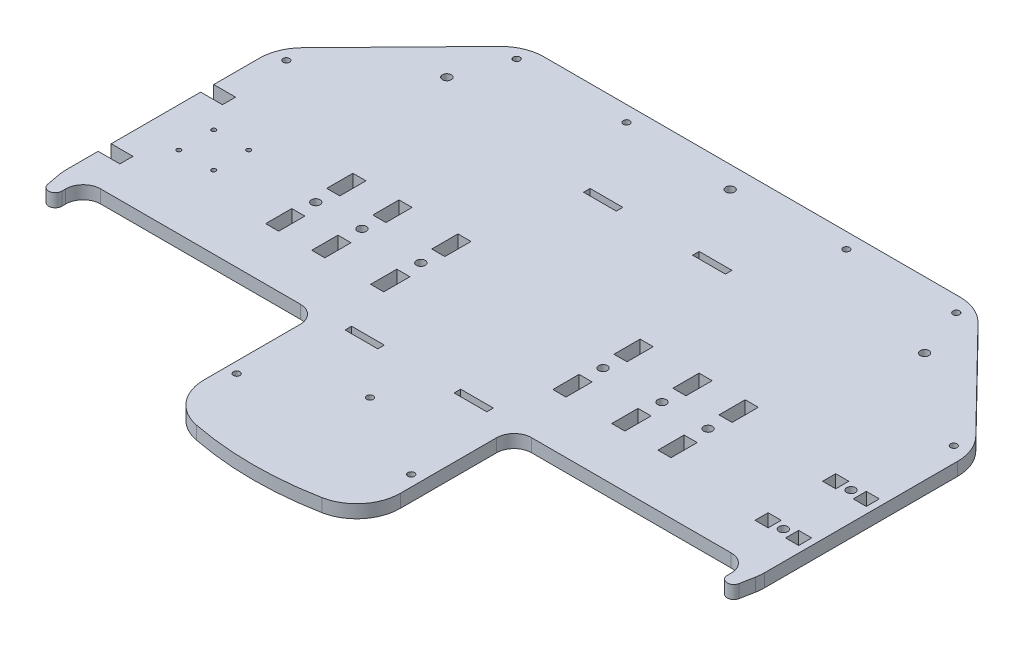
SolidWorks part; units mm, degrees
material "Hêtre"
ref_plane "Plan de face" through (0, 0, 0) normal (0, 0, 1) x (1, 0, 0)
ref_plane "Plan de dessus" through (0, 0, 0) normal (0, 1, 0) x (1, 0, 0)
ref_plane "Plan de droite" through (0, 0, 0) normal (1, 0, 0) x (0, 0, -1)
sketch "Esquisse1" plane through (0, 0, 0) normal (0, 1, 0) x (1, 0, 0)
  line L0 (-159.6514, 61.9965) -> (-151.003, 16.2822)
  line L1 (131.3515, 0) -> (50.1768, 0)
  line L2 (0, 0) -> (0, 220) construction
  line L3 (95.3188, 220) -> (-95.3188, 220)
  line L4 (-160, 65.7142) -> (-160, 154.2858)
  line L5 (-154.3028, 168.2654) -> (-109.6216, 213.9796)
  line L6 (0, 110) -> (-160, 110) construction
  line L7 (154.3028, 168.2654) -> (109.6216, 213.9796)
  line L8 (160, 65.7142) -> (160, 154.2858)
  line L9 (159.6514, 61.9965) -> (151.003, 16.2822)
  line L10 (-50.1768, 0) -> (-131.3515, 0)
  arc A0 (-151.003, 16.2822) -> (-131.3515, 0) centre (-131.3515, 20) ccw
  arc A1 (-159.6514, 61.9965) -> (-160, 65.7142) centre (-140, 65.7142) cw
  arc A2 (-109.6216, 213.9796) -> (-95.3188, 220) centre (-95.3188, 200) cw
  arc A3 (-154.3028, 168.2654) -> (-160, 154.2858) centre (-140, 154.2858) ccw
  arc A4 (154.3028, 168.2654) -> (160, 154.2858) centre (140, 154.2858) cw
  arc A5 (109.6216, 213.9796) -> (95.3188, 220) centre (95.3188, 200) ccw
  arc A6 (159.6514, 61.9965) -> (160, 65.7142) centre (140, 65.7142) ccw
  arc A7 (151.003, 16.2822) -> (131.3515, 0) centre (131.3515, 20) cw
  arc A8 (-50.1768, 0) -> (50.1768, 0) centre (0, 142.6245) ccw
  dimension "D3" = 20
  dimension "D1" = 220
  dimension "D2" = 160
extrude "Boss.-Extru.1" add sketch "Esquisse1" along normal blind 6
sketch "Esquisse4" plane through (0, 6, 0) normal (0, 1, 0) x (1, 0, 0)
  line L0 (0, 0) -> (0, 90.3971) construction
  line L1 (-152.5, -4) -> (-45, -4)
  line L2 (-152.5, -4) -> (-152.5, 66)
  line L3 (-152.5, 66) -> (-45, 66)
  line L4 (-45, -4) -> (-45, 66)
  line L5 (45, -4) -> (45, 66)
  line L6 (152.5, 66) -> (45, 66)
  line L7 (152.5, -4) -> (152.5, 66)
  line L8 (152.5, -4) -> (45, -4)
  dimension "D1" = 70
  dimension "D2" = 107.5
  dimension "D3" = 45
  dimension "D4" = 66
extrude "Enlèv. mat.-Extru.3" cut sketch "Esquisse4" against normal blind 6
fillet "Congé1" radius 20 2 edges at (45, 3, 1.717) (-45, 3, 1.717)
fillet "Congé2" radius 8 4 edges at (152.5, 3, -66) (45, 3, -66) (-45, 3, -66) (-152.5, 3, -66)
fillet "Congé3" radius 3 2 edges at (152.5, 3, -24.1954) (-152.5, 3, -24.1954)
sketch "Esquisse7" plane through (0, 6, 0) normal (0, 1, 0) x (1, 0, 0)
  line L0 (-53, 69) -> (53, 69) construction
  line L1 (0, 69) -> (0, -8.569) construction
  line L2 (-32.5, 69) -> (-17.5, 69)
  line L3 (-32.5, 69) -> (-32.5, 66)
  line L4 (-32.5, 66) -> (-17.5, 66)
  line L5 (-17.5, 69) -> (-17.5, 66)
  line L6 (17.5, 69) -> (17.5, 66)
  line L7 (32.5, 66) -> (17.5, 66)
  line L8 (32.5, 69) -> (32.5, 66)
  line L9 (32.5, 69) -> (17.5, 69)
  arc A2 (-28.8112, -5.7985) -> (28.8112, -5.7985) centre (0, 142.6245) ccw construction
  point P13 (-25, 69)
  point P18 (25, 66)
  dimension "D1" = 15
  dimension "D2" = 77.569
  dimension "D3" = 3
extrude "Enlèv. mat.-Extru.6" cut sketch "Esquisse7" against normal blind 10
sketch "Esquisse6" plane through (0, 6, 0) normal (0, 1, 0) x (1, 0, 0)
  line L0 (0, 220) -> (0, 187.6823) construction
  line L1 (95.3188, 220) -> (-95.3188, 220) construction
  circle A0 centre (0, 210) radius 2
  dimension "D1" = 4
  dimension "D2" = 10
extrude "Enlèv. mat.-Extru.5" cut sketch "Esquisse6" against normal blind 10
sketch "Esquisse8" plane through (0, 6, 0) normal (0, 1, 0) x (1, 0, 0)
  line L0 (-160, 110) -> (160, 110) construction
  line L1 (-160, 154.2858) -> (-160, 65.7142) construction
  line L2 (160, 65.7142) -> (160, 154.2858) construction
  line L3 (-86.9, 90) -> (-86.9, 102)
  line L4 (-92.9, 130) -> (-86.9, 130)
  line L5 (-92.9, 130) -> (-92.9, 118)
  line L6 (-92.9, 118) -> (-86.9, 118)
  line L7 (-86.9, 130) -> (-86.9, 118)
  line L8 (-92.9, 102) -> (-86.9, 102)
  line L9 (-92.9, 90) -> (-92.9, 102)
  line L10 (-92.9, 90) -> (-86.9, 90)
  line L11 (-65.76, 90) -> (-65.76, 102)
  line L12 (-71.76, 130) -> (-65.76, 130)
  line L13 (-71.76, 130) -> (-71.76, 118)
  line L14 (-71.76, 118) -> (-65.76, 118)
  line L15 (-65.76, 130) -> (-65.76, 118)
  line L16 (-71.76, 102) -> (-65.76, 102)
  line L17 (-71.76, 90) -> (-71.76, 102)
  line L18 (-71.76, 90) -> (-65.76, 90)
  line L19 (-38.76, 90) -> (-38.76, 102)
  line L20 (-44.76, 130) -> (-38.76, 130)
  line L21 (-44.76, 130) -> (-44.76, 118)
  line L22 (-44.76, 118) -> (-38.76, 118)
  line L23 (-38.76, 130) -> (-38.76, 118)
  line L24 (-44.76, 102) -> (-38.76, 102)
  line L25 (-44.76, 90) -> (-44.76, 102)
  line L26 (-44.76, 90) -> (-38.76, 90)
  line L27 (0, 110) -> (0, 51.8144) construction
  line L28 (44.76, 90) -> (38.76, 90)
  line L29 (44.76, 90) -> (44.76, 102)
  line L30 (44.76, 102) -> (38.76, 102)
  line L31 (38.76, 130) -> (38.76, 118)
  line L32 (44.76, 118) -> (38.76, 118)
  line L33 (44.76, 130) -> (44.76, 118)
  line L34 (44.76, 130) -> (38.76, 130)
  line L35 (38.76, 90) -> (38.76, 102)
  line L36 (71.76, 90) -> (65.76, 90)
  line L37 (71.76, 90) -> (71.76, 102)
  line L38 (71.76, 102) -> (65.76, 102)
  line L39 (65.76, 130) -> (65.76, 118)
  line L40 (71.76, 118) -> (65.76, 118)
  line L41 (71.76, 130) -> (71.76, 118)
  line L42 (71.76, 130) -> (65.76, 130)
  line L43 (65.76, 90) -> (65.76, 102)
  line L44 (92.9, 90) -> (86.9, 90)
  line L45 (92.9, 90) -> (92.9, 102)
  line L46 (92.9, 102) -> (86.9, 102)
  line L47 (86.9, 130) -> (86.9, 118)
  line L48 (92.9, 118) -> (86.9, 118)
  line L49 (92.9, 130) -> (92.9, 118)
  line L50 (92.9, 130) -> (86.9, 130)
  line L51 (86.9, 90) -> (86.9, 102)
  line L52 (-89.9, 118) -> (-89.9, 102) construction
  line L53 (-68.76, 118) -> (-68.76, 102) construction
  line L54 (-41.76, 118) -> (-41.76, 102) construction
  circle A0 centre (-89.9, 110) radius 2
  circle A1 centre (-68.76, 110) radius 2
  circle A2 centre (-41.76, 110) radius 2
  circle A3 centre (41.76, 110) radius 2
  circle A4 centre (68.76, 110) radius 2
  circle A5 centre (89.9, 110) radius 2
  dimension "D7" = 4
  dimension "D8" = 4
  dimension "D9" = 4
  dimension "D1" = 6
  dimension "D2" = 12
  dimension "D3" = 67.1
  dimension "D4" = 8
  dimension "D5" = 2
  dimension "D6" = 2
extrude "Enlèv. mat.-Extru.7" cut sketch "Esquisse8" against normal blind 10
sketch "Esquisse9" plane through (0, 6, 0) normal (0, 1, 0) x (1, 0, 0)
  line L0 (160, 65.7142) -> (160, 154.2858) construction
  line L1 (151, 121.4) -> (157, 121.4)
  line L2 (151, 121.4) -> (151, 115.4)
  line L3 (151, 115.4) -> (157, 115.4)
  line L4 (157, 121.4) -> (157, 115.4)
  line L5 (151, 90.4) -> (157, 90.4)
  line L6 (151, 90.4) -> (151, 84.4)
  line L7 (151, 84.4) -> (157, 84.4)
  line L8 (157, 90.4) -> (157, 84.4)
  line L9 (95.3188, 220) -> (-95.3188, 220) construction
  line L10 (143, 118.4) -> (151, 118.4) construction
  line L11 (143, 121.4) -> (137, 121.4)
  line L12 (143, 121.4) -> (143, 115.4)
  line L13 (143, 115.4) -> (137, 115.4)
  line L14 (137, 121.4) -> (137, 115.4)
  line L15 (143, 90.4) -> (137, 90.4)
  line L16 (143, 90.4) -> (143, 84.4)
  line L17 (143, 84.4) -> (137, 84.4)
  line L18 (137, 90.4) -> (137, 84.4)
  line L19 (143, 87.4) -> (151, 87.4) construction
  circle A0 centre (147, 118.4) radius 2
  circle A1 centre (147, 87.4) radius 2
  dimension "D9" = 4
  dimension "D10" = 4
  dimension "D1" = 6
  dimension "D2" = 3
  dimension "D3" = 6
  dimension "D4" = 6
  dimension "D5" = 37
  dimension "D6" = 98.6
  dimension "D7" = 8
  dimension "D8" = 6
extrude "Enlèv. mat.-Extru.8" cut sketch "Esquisse9" against normal blind 10
sketch "Esquisse10" plane through (0, 6, 0) normal (0, 1, 0) x (1, 0, 0)
  line L0 (-144.4656, 178.33) -> (144.4656, 178.33) construction
  line L1 (-109.6216, 213.9796) -> (-154.3028, 168.2654) construction
  line L2 (154.3028, 168.2654) -> (109.6216, 213.9796) construction
  line L3 (95.3188, 220) -> (-95.3188, 220) construction
  line L4 (0, 220) -> (0, 178.33) construction
  line L6 (-32.5, 178.33) -> (-17.5, 178.33)
  line L7 (-32.5, 178.33) -> (-32.5, 175.33)
  line L8 (-32.5, 175.33) -> (-17.5, 175.33)
  line L9 (-17.5, 178.33) -> (-17.5, 175.33)
  line L10 (17.5, 178.33) -> (32.5, 178.33)
  line L11 (17.5, 178.33) -> (17.5, 175.33)
  line L12 (17.5, 175.33) -> (32.5, 175.33)
  line L13 (32.5, 178.33) -> (32.5, 175.33)
  dimension "D1" = 41.67
  dimension "D2" = 3
  dimension "D3" = 17.5
  dimension "D4" = 15
  dimension "D5" = 15
  dimension "D6" = 3
  dimension "D7" = 17.5
extrude "Enlèv. mat.-Extru.9" cut sketch "Esquisse10" against normal blind 10
sketch "Esquisse11" plane through (0, 6, 0) normal (0, 1, 0) x (-1, 0, 0)
  line L0 (45, -23.835) -> (-45, -23.835) construction
  line L1 (45, -13.835) -> (45, -58) construction
  line L2 (-45, -58) -> (-45, -13.835) construction
  line L3 (0, -23.835) -> (0, 8.569) construction
  line L4 (103.0779, -218.4336) -> (95.3188, -200) construction
  line L5 (0, -220) -> (0, -179) construction
  line L6 (-95.3188, -220) -> (95.3188, -220) construction
  line L7 (160, -154.2858) -> (160, -65.7142) construction
  line L8 (158.521, -161.8337) -> (140, -154.2858) construction
  line L9 (100.7502, -212.9035) -> (0, -212.9035) construction
  line L10 (142, -99.3242) -> (126, -99.3242) construction
  line L11 (142, -99.3242) -> (142, -115.3242) construction
  line L12 (142, -115.3242) -> (126, -115.3242) construction
  line L13 (126, -99.3242) -> (126, -115.3242) construction
  line L15 (160, -133.3242) -> (150, -133.3242)
  line L16 (160, -133.3242) -> (160, -127.3242)
  line L17 (160, -127.3242) -> (150, -127.3242)
  line L18 (150, -133.3242) -> (150, -127.3242)
  line L19 (160, -86.3242) -> (150, -86.3242)
  line L20 (160, -86.3242) -> (160, -80.3242)
  line L21 (160, -80.3242) -> (150, -80.3242)
  line L22 (150, -86.3242) -> (150, -80.3242)
  circle A0 centre (40, -23.835) radius 1.5
  arc A1 (28.8112, 5.7985) -> (-28.8112, 5.7985) centre (0, -142.6245) ccw construction
  circle A2 centre (-40, -23.835) radius 1.5
  arc A3 (95.3188, -220) -> (109.6216, -213.9796) centre (95.3188, -200) ccw construction
  circle A4 centre (100.7502, -212.9035) radius 1.5
  arc A5 (154.3028, -168.2654) -> (160, -154.2858) centre (140, -154.2858) ccw construction
  circle A6 centre (152.9647, -159.5693) radius 1.5
  circle A7 centre (50.3751, -212.9035) radius 1.5
  circle A8 centre (-152.9647, -159.5693) radius 1.5
  circle A9 centre (-100.7502, -212.9035) radius 1.5
  circle A10 centre (-50.3751, -212.9035) radius 1.5
  circle A11 centre (0, -44.911) radius 1.5
  circle A12 centre (-109.4788, -189.64) radius 2
  circle A13 centre (109.4788, -189.64) radius 2
  circle A14 centre (142, -99.3242) radius 1
  circle A15 centre (126, -99.3242) radius 1
  circle A16 centre (126, -115.3242) radius 1
  circle A17 centre (142, -115.3242) radius 1
  dimension "D2" = 3
  dimension "D4" = 3
  dimension "D6" = 3
  dimension "D8" = 3
  dimension "D9" = 3
  dimension "D13" = 4
  dimension "D18" = 2
  dimension "D19" = 2
  dimension "D20" = 2
  dimension "D21" = 2
  dimension "D1" = 10
  dimension "D3" = 5
  dimension "D5" = 14
  dimension "D7" = 14
  dimension "D10" = 53.48
  dimension "D11" = 14.16
  dimension "D12" = 30.36
  dimension "D14" = 16
  dimension "D15" = 16
  dimension "D16" = 49.61
  dimension "D17" = 18
  dimension "D22" = 10
  dimension "D23" = 6
  dimension "D24" = 10
  dimension "D25" = 6
  dimension "D26" = 12
  dimension "D27" = 13
extrude "Enlèv. mat.-Extru.10" cut sketch "Esquisse11" against normal blind 10
